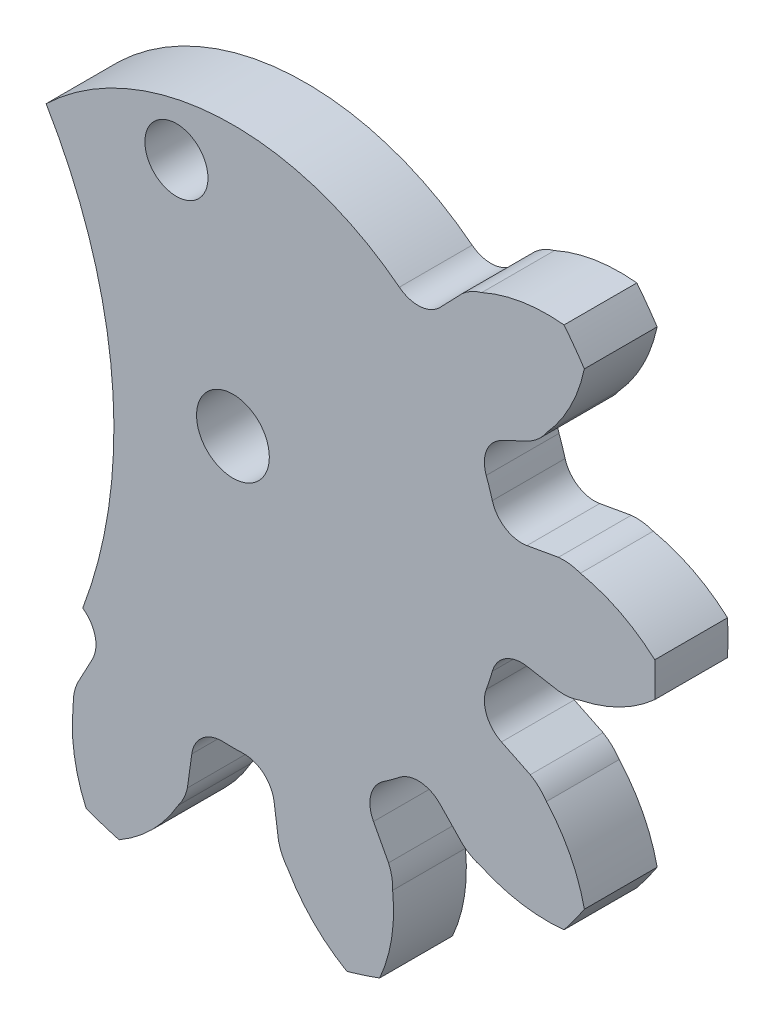
SolidWorks part; units mm, degrees
material "Acrílico (médio-alto impacto)"
ref_plane "Plano frontal" through (0, 0, 0) normal (0, 0, 1) x (1, 0, 0)
ref_plane "Plano superior" through (0, 0, 0) normal (0, 1, 0) x (1, 0, 0)
ref_plane "Plano direito" through (0, 0, 0) normal (1, 0, 0) x (0, 0, -1)
sketch "Posicionamentos" plane through (0, 0, 0) normal (0, 0, 1) x (1, 0, 0)
  circle A0 centre (0, 0) radius 17.4
  circle A1 centre (0, 0) radius 14.5
  circle A2 centre (0, 0) radius 11.1157
  circle A3 centre (0, 0) radius 13.6255
  dimension "De" = 34.8
  dimension "DP" = 29
  dimension "DI" = 22.2314
  dimension "DB" = 27.2511
sketch "Dente" plane through (0, 0, 0) normal (0, 0, 1) x (1, 0, 0)
  line L0 (0, 0) -> (0, 17.4) construction
  line L1 (0, 0) -> (17.4, 0) construction
  line L2 (13.4152, -2.3849) -> (10.9441, -1.9456)
  line L3 (14.3215, -2.2683) -> (0, 0) construction
  line L4 (13.4152, 2.3849) -> (10.9441, 1.9456)
  circle A0 centre (0, 0) radius 17.4 construction
  arc A1 (17.3854, -0.7115) -> (14.3215, -2.2683) centre (12.9613, 4.2023) cw
  circle A2 centre (0, 0) radius 14.5 construction
  arc A3 (14.3215, -2.2683) -> (13.4152, -2.3849) centre (13.6198, -0.3943) cw
  circle A4 centre (0, 0) radius 13.6255 construction
  circle A5 centre (0, 0) radius 11.1157 construction
  arc A6 (14.3215, 2.2683) -> (13.4152, 2.3849) centre (13.6198, 0.3943) ccw
  arc A7 (17.3854, 0.7115) -> (14.3215, 2.2683) centre (12.9613, -4.2023) ccw
  arc A8 (10.9441, 1.9456) -> (10.9441, -1.9456) centre (0, 0) cw
  arc A9 (17.3854, 0.7115) -> (17.3854, -0.7115) centre (0, 0) cw
  arc A10 (14.3215, 2.2683) -> (14.3215, -2.2683) centre (0, 0) cw construction
  dimension "R" = 6.612
  dimension "R1" = 2.001
  dimension "alpha" = 9
  dimension "Aposicionador" = 270
  dimension "D1" = 4.5553
sketch "Furo" plane through (0, 0, 0) normal (0, 0, 1) x (1, 0, 0)
  line L0 (0, 0) -> (-2.3294, 8.6933) construction
  line L2 (0, -1.65) -> (0, 1.65) construction
  circle A0 centre (0, 0) radius 9
  dimension "D2" = 18
  dimension "D1" = 15
sketch "Esboço9" plane through (0, 0, 0) normal (0, 0, 1) x (1, 0, 0)
  line L0 (-24.9049, -2.1789) -> (0, 0) construction
  line L2 (0, 0) -> (-21.996, 0) construction
  circle A0 centre (-24.9049, -2.1789) radius 20
  dimension "D2" = 40
  dimension "D1" = 5
  dimension "D3" = 25
extrude "Base" add sketch "Posicionamentos" along normal blind 3 contours A2
hole_wizard "Furo de diâmetro Ø2.6 (2.6)1" positions "Esboço7" profile "Esboço8" hole size "Ø2.6" standard "ISO" end condition through all
sketch "Esboço7" plane through (0, 0, 3) normal (0, 0, 1) x (1, 0, 0)
  point P0 (-2.3294, 8.6933)
sketch "Esboço8" plane through (-2.3294, 8.6933, 3) normal (1, 0, 0) x (0, -1, 0)
  line L0 (0, 0) -> (0, 3)
  line L1 (0, 3) -> (1.3, 3)
  line L2 (1.3, 3) -> (1.3, 0)
  line L5 (1.3, 0) -> (0, 0)
  line L11 (0, -6.35) -> (0, 107.95) construction
  dimension "Thru Hole Dia." = 2.6
  dimension "Thru Hole Depth" = 3
extrude "Base Dente" add sketch "Dente" along normal through all
fillet "Raio Dente" radius 1.2549 2 edges at (10.9441, 1.9456, 1.5) (10.9441, -1.9456, 1.5)
pattern_circular "PadrãoCircular1" count 10 over 360 about axis through (0, 0, 0) along (0, 0, 1) skipping 4, 5, 6, 7, 8 of "Base Dente", "Raio Dente"
hole_wizard "Furo de diâmetro Ø3.0 (3)1" positions "Esboço4" profile "Esboço5" hole size "Ø3.0" standard "ISO" end condition through all
sketch "Esboço4" plane through (0, 0, 3) normal (0, 0, 1) x (1, 0, 0)
  point P0 (0, 0)
sketch "Esboço5" plane through (0, 0, 3) normal (1, 0, 0) x (0, -1, 0)
  line L0 (0, 0) -> (0, 3)
  line L1 (0, 3) -> (1.5, 3)
  line L2 (1.5, 3) -> (1.5, 0)
  line L5 (1.5, 0) -> (0, 0)
  line L11 (0, -6.35) -> (0, 107.95) construction
  dimension "Thru Hole Dia." = 3
  dimension "Thru Hole Depth" = 3
extrude "Corte-extrusão1" cut sketch "Esboço9" along normal through all contours A0
equation "\"Z\"= 10"
equation "\"M\"= 2.9'Módulo"
equation "\"DP\"= \"Z\" * \"M\""
equation "\"P\"= \"M\" * pi'Passo"
equation "\"S\"= \"P\" / 2'Espessura Circular"
equation "\"V\"= \"S\"'Vão"
equation "\"sc\"= 1"
equation "\"de\"= \"M\" * ( \"Z\" + 2 )'Diâmetro Externo"
equation "\"di\"= \"M\" * ( \"Z\" - 2.334 )'Diâmetro Interno"
equation "\"Phi\"= 20'ângulo de pressão"
equation "\"db\"= \"DP\" * cos ( \"Phi\" )'Diâmetro do círculo de base"
equation "\"a\"= \"M\"'Altura da cabeça do dente"
equation "\"b\"= 1.167 * \"M\"'Altura do pé do dente"
equation "\"h\"= \"a\" + \"b\"'Altura do dente"
equation "\"e\"= .167 * \"M\"'Folga no pé do dente"
equation "\"alpha\"= 90 / \"Z\"'ângulo do dente"
equation "\"f\"= \"ValorF@Padrão\""
equation "\"f1\"= \"ValorF1@Padrão\""
equation "\"r\"= \"f\" * \"M\" 'Raio do dente"
equation "\"r1\"= \"f1\" * \"M\"'Rario 1 do dente"
equation "\"De@Posicionamentos\" = \"de\""
equation "\"DP@Posicionamentos\" = \"DP\""
equation "\"DI@Posicionamentos\" = \"di\""
equation "\"DB@Posicionamentos\" = \"db\""
equation "\"R@Dente\" = \"r\""
equation "\"R1@Dente\" = \"r1\""
equation "\"alpha@Dente\" = \"alpha\""
equation "\"D1@PadrãoCircular1\"=\"Z\""
equation "\"rd\"= ( \"db\" - \"di\" ) / 4"
equation "\"D1@Raio Dente\"=\"rd\""
equation "\"Posicionador\"= 1"
equation "\"Aposicionador\"= IIF ( \"Posicionador\" = 0 , 0 , ( \"alpha\" * 2 ) )"
equation "\"D1@Dente\"=\"S\""
